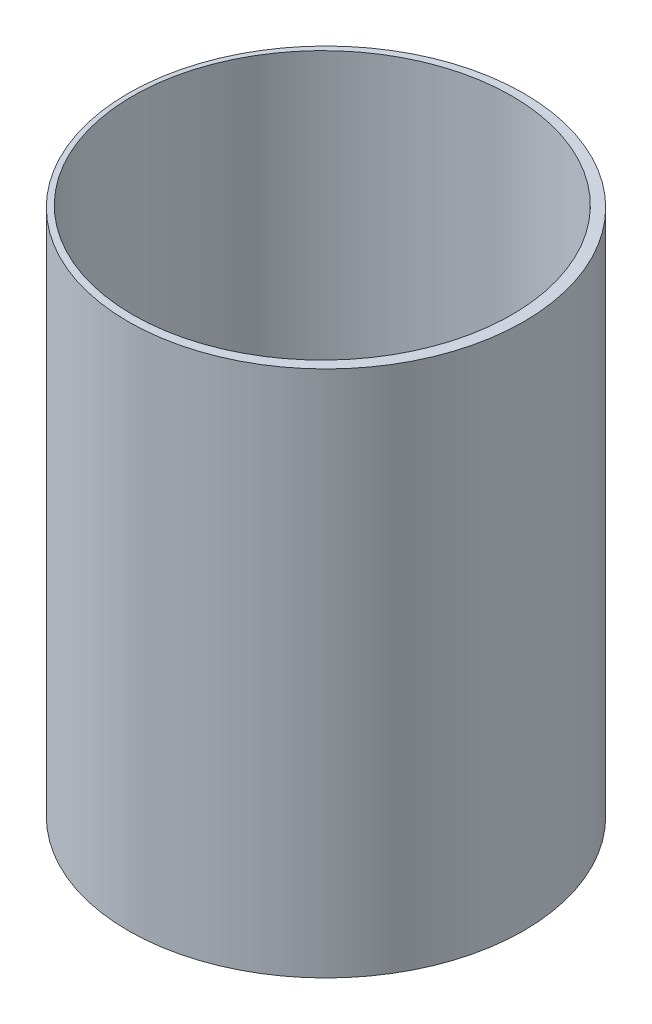
SolidWorks part; units mm, degrees
ref_plane "Front Plane" through (0, 0, 0) normal (0, 0, 1) x (1, 0, 0)
ref_plane "Top Plane" through (0, 0, 0) normal (0, 1, 0) x (1, 0, 0)
ref_plane "Right Plane" through (0, 0, 0) normal (1, 0, 0) x (0, 0, -1)
sketch "Sketch1" plane through (0, 0, 0) normal (0, 1, 0) x (1, 0, 0)
  circle A0 centre (0, 0) radius 57.15
  dimension "D1" = 114.3
extrude "Boss-Extrude1" add sketch "Sketch1" along normal blind 152.4
sketch "Sketch4" plane through (0, 152.4, 0) normal (0, 1, 0) x (1, 0, 0)
  circle A0 centre (-1.0637, 0) radius 54.7687
  dimension "D1" = 109.5375
extrude "Cut-Extrude2" cut sketch "Sketch4" against normal blind 254
